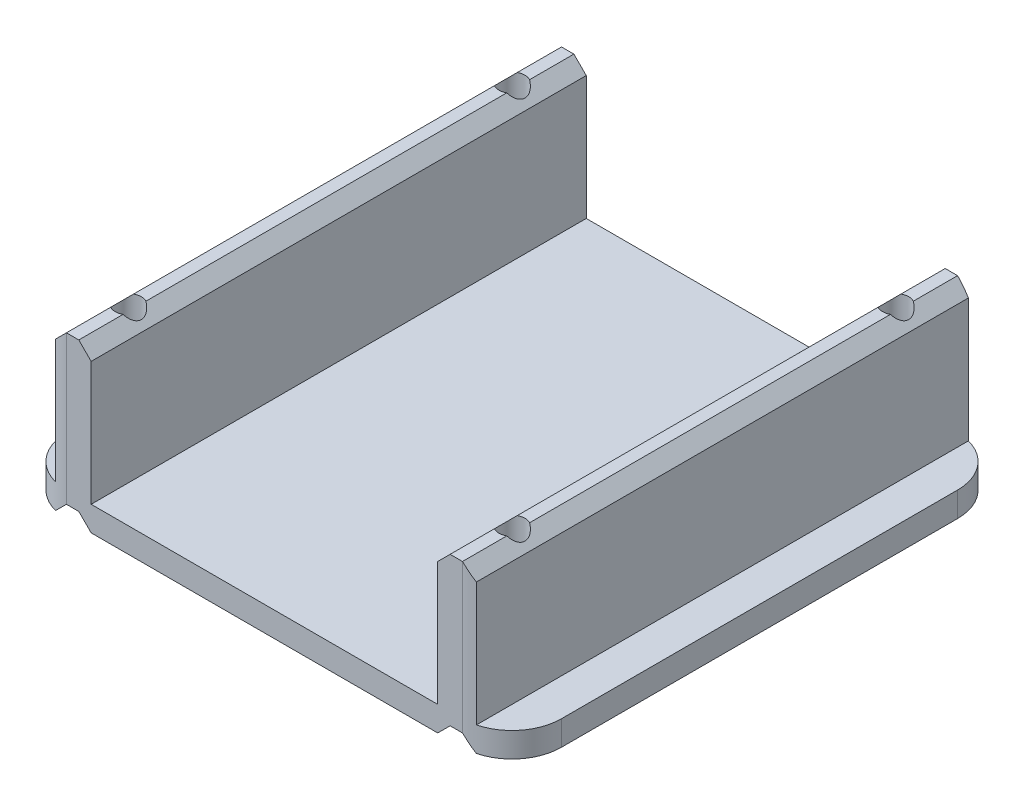
SolidWorks part; units mm, degrees
ref_plane "Front Plane" through (0, 0, 0) normal (0, 0, 1) x (1, 0, 0)
ref_plane "Top Plane" through (0, 0, 0) normal (0, 1, 0) x (1, 0, 0)
ref_plane "Right Plane" through (0, 0, 0) normal (1, 0, 0) x (0, 0, -1)
sketch "Sketch1" plane through (0, 0, 0) normal (0, 1, 0) x (1, 0, 0)
  line L1 (-20, -20) -> (20, -20)
  line L2 (-20, -20) -> (-20, 20)
  line L3 (-20, 20) -> (20, 20)
  line L4 (20, -20) -> (20, 20)
  line L5 (-20, -20) -> (20, 20) construction
  line L6 (-20, 20) -> (20, -20) construction
  point P0 (0, 0)
  dimension "D1" = 40
extrude "Boss-Extrude1" add sketch "Sketch1" along normal blind 2
sketch "Sketch2" plane through (0, 0, 20) normal (0, 0, 1) x (1, 0, 0)
  line L0 (14, 0) -> (15, 1)
  line L1 (-20, 0) -> (20, 0) construction
  line L2 (15, 1) -> (16, 1)
  line L3 (16, 1) -> (17, 0)
  line L4 (17, 0) -> (14, 0)
  point P10 (0, 0)
  point P14 (0, 0)
  dimension "D1" = 14
  dimension "D2" = 3
  dimension "D3" = 1
  dimension "D5" = 45
extrude "Cut-Extrude1" cut sketch "Sketch2" against normal through all
sketch "Sketch3" plane through (0, 0, 20) normal (0, 0, 1) x (1, 0, 0)
  line L0 (14, 12) -> (17, 12) construction
  line L2 (17, 12) -> (16, 13)
  line L3 (16, 13) -> (15, 13)
  line L4 (15, 13) -> (14, 12)
  line L5 (14, 12) -> (14, 2)
  line L6 (-20, 2) -> (20, 2) construction
  line L7 (14, 2) -> (17, 2)
  line L8 (17, 2) -> (17, 12)
  dimension "D1" = 3
  dimension "D2" = 45
  dimension "D3" = 14
  dimension "D4" = 1
  dimension "D5" = 10
extrude "Boss-Extrude2" add sketch "Sketch3" along normal up to surface (40 mm away)
mirror "Mirror2" about plane through (0, 0, 0) normal (1, 0, 0) of "Boss-Extrude2", "Cut-Extrude1"
fillet "Fillet1" radius 4 4 edges at (-20, 1, 20) (20, 1, 20) (20, 1, -20) (-20, 1, -20)
sketch "Sketch6" plane through (0, 0, 0) normal (0, 1, 0) x (1, 0, 0)
  line L1 (15.5, -15.5) -> (-15.5, -15.5) construction
  line L2 (15.5, -15.5) -> (15.5, 15.5) construction
  line L3 (15.5, 15.5) -> (-15.5, 15.5) construction
  line L4 (-15.5, -15.5) -> (-15.5, 15.5) construction
  line L5 (15.5, -15.5) -> (-15.5, 15.5) construction
  line L6 (15.5, 15.5) -> (-15.5, -15.5) construction
  circle A0 centre (-15.5, 15.5) radius 1.05
  circle A1 centre (15.5, 15.5) radius 1.05
  circle A2 centre (-15.5, -15.5) radius 1.05
  circle A3 centre (15.5, -15.5) radius 1.05
  point P0 (0, 0)
  dimension "D2" = 2.1
  dimension "D1" = 31
extrude "Cut-Extrude4" cut sketch "Sketch6" along normal through all
